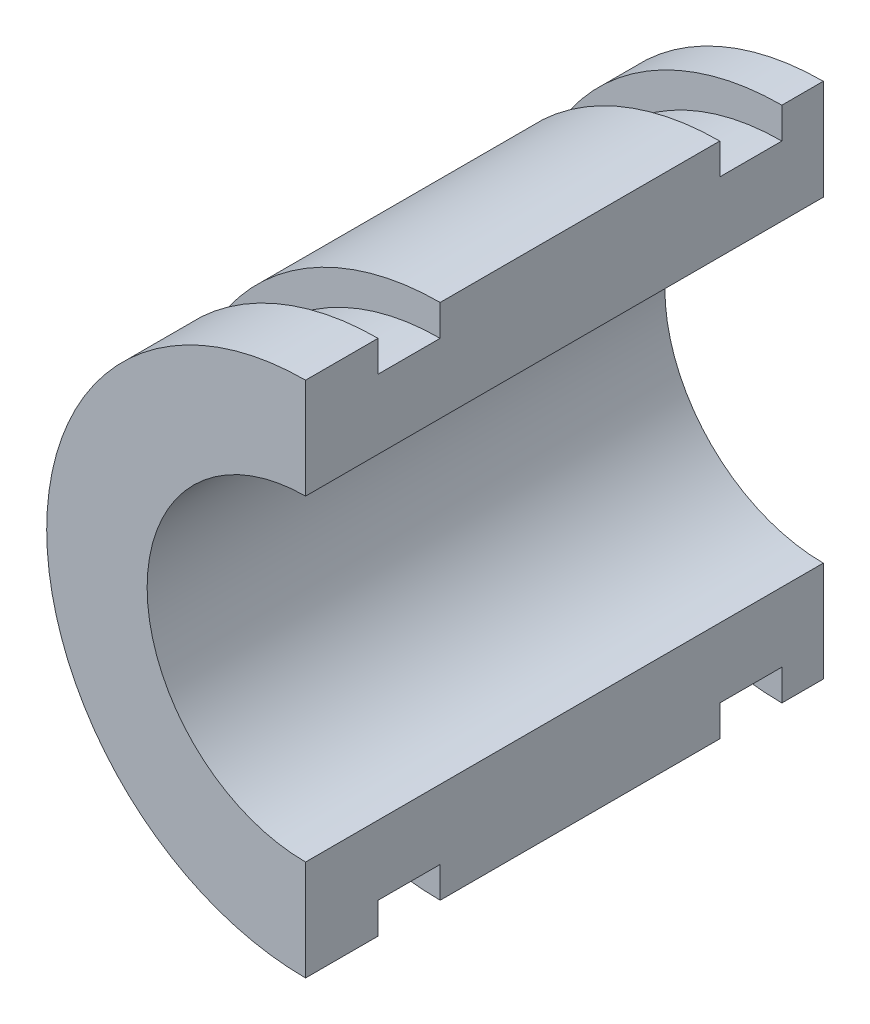
SolidWorks part; units mm, degrees
ref_plane "Ön Düzlem" through (0, 0, 0) normal (0, 0, 1) x (1, 0, 0)
ref_plane "Üst Düzlem" through (0, 0, 0) normal (0, 1, 0) x (1, 0, 0)
ref_plane "Sağ Düzlem" through (0, 0, 0) normal (1, 0, 0) x (0, 0, -1)
sketch "Çizim1" plane through (0, 0, 0) normal (0, 0, 1) x (1, 0, 0)
  line L0 (0, 12.5) -> (0, 7.65)
  line L1 (0, -7.65) -> (0, -12.5)
  arc A0 (0, -12.5) -> (0, 12.5) centre (0, 0) cw
  arc A1 (0, 7.65) -> (0, -7.65) centre (0, 0) ccw
  dimension "D1" = 12.5
  dimension "D2" = 7.65
extrude "Yükseklik-Ekstrüzyon1" add sketch "Çizim1" along normal blind 25
sketch "Çizim2" plane through (0, 0, 0) normal (1, 0, 0) x (0, 0, -1)
  line L0 (-25, 12.5) -> (0, 12.5) construction
  line L1 (-21.5, 12.5) -> (-18.5, 12.5)
  line L2 (-21.5, 12.5) -> (-21.5, 11)
  line L3 (-21.5, 11) -> (-18.5, 11)
  line L4 (-18.5, 12.5) -> (-18.5, 11)
  line L5 (0, 7.65) -> (0, 12.5) construction
  line L6 (-5, 12.5) -> (-2, 12.5)
  line L7 (-5, 12.5) -> (-5, 11)
  line L8 (-5, 11) -> (-2, 11)
  line L9 (-2, 12.5) -> (-2, 11)
  line L10 (0, 0) -> (-28.9703, 0) construction
  dimension "D1" = 2
  dimension "D2" = 3
  dimension "D3" = 13.5
  dimension "D4" = 1.5
revolve "Kes-Döndür1" cut sketch "Çizim2" angle 360 about L10
